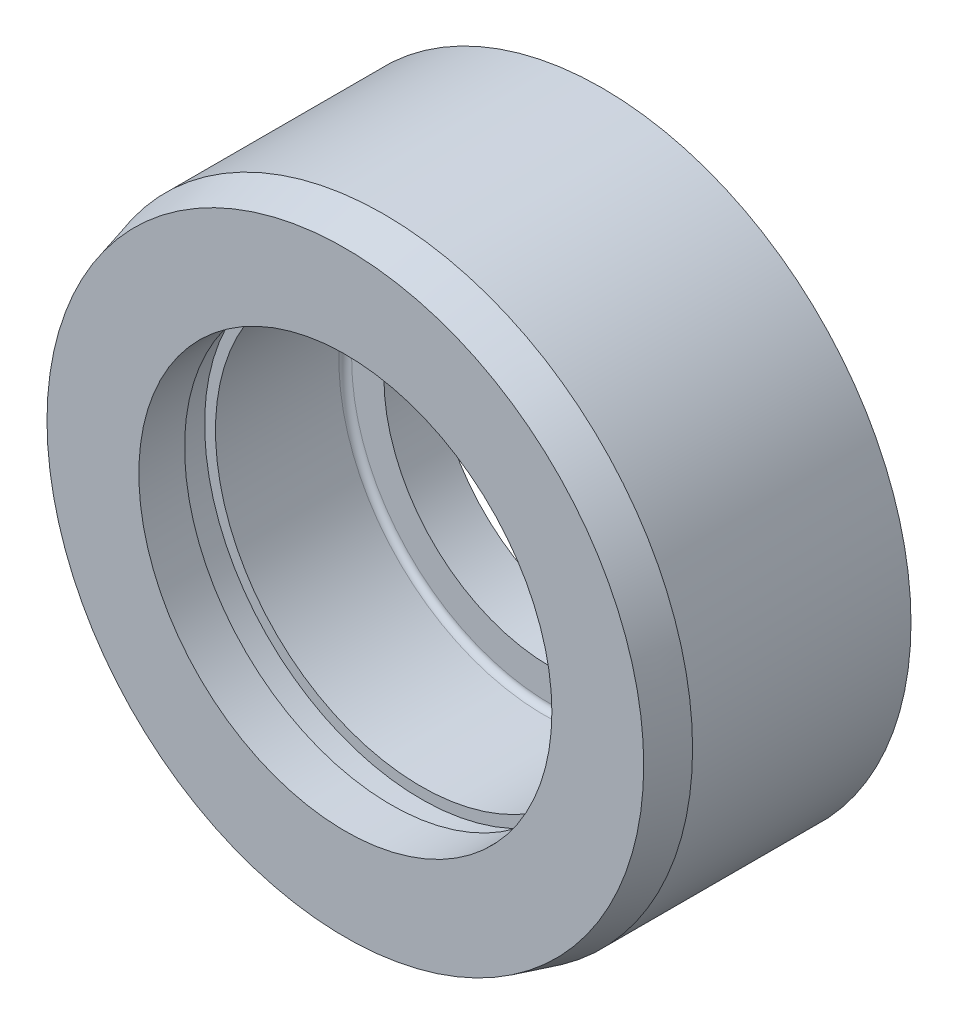
SolidWorks part; units mm, degrees
material "1023 Carbon Steel Sheet (SS)"
ref_plane "Front Plane" through (0, 0, 0) normal (0, 0, 1) x (1, 0, 0)
ref_plane "Top Plane" through (0, 0, 0) normal (0, 1, 0) x (1, 0, 0)
ref_plane "Right Plane" through (0, 0, 0) normal (1, 0, 0) x (0, 0, -1)
sketch "Sketch1" plane through (0, 0, 0) normal (0, 0, 1) x (1, 0, 0)
  circle A0 centre (0, 0) radius 12.0135
  dimension "D3" = 24.027
extrude "Extrude1" add sketch "Sketch1" along normal blind 10
sketch "Sketch3" plane through (0, 0, 10) normal (0, 0, 1) x (1, 0, 0)
  circle A0 centre (0, 0) radius 8.0045
  circle A1 centre (0, 0) radius 12.0135 construction
  dimension "D1" = 16.009
extrude "Extrude2" cut sketch "Sketch3" against normal blind 8
sketch "Sketch4" plane through (0, 0, 2) normal (0, 0, 1) x (1, 0, 0)
  circle A0 centre (0, 0) radius 6.5
  dimension "D1" = 13
extrude "Extrude3" cut sketch "Sketch4" against normal through all
fillet "Fillet1" radius 0.25 1 edges at (8.0045, 0, 2)
sketch "Sketch5" plane through (0, 0, 10) normal (0, 0, 1) x (1, 0, 0)
  circle A0 centre (0, 0) radius 8.4275
  dimension "D1" = 16.855
extrude "Extrude4" cut sketch "Sketch5" against normal blind 1.17 from offset 1.78 offset against normal yes
sketch "Sketch6" plane through (0, 0, 10) normal (0, 0, 1) x (1, 0, 0)
  circle A0 centre (0, 0) radius 8.0375
  dimension "D1" = 16.075
extrude "Extrude5" cut sketch "Sketch6" against normal up to next
chamfer "Chamfer2" distance 1.5 angle 15 1 edges at (12.0135, 0, 10)
